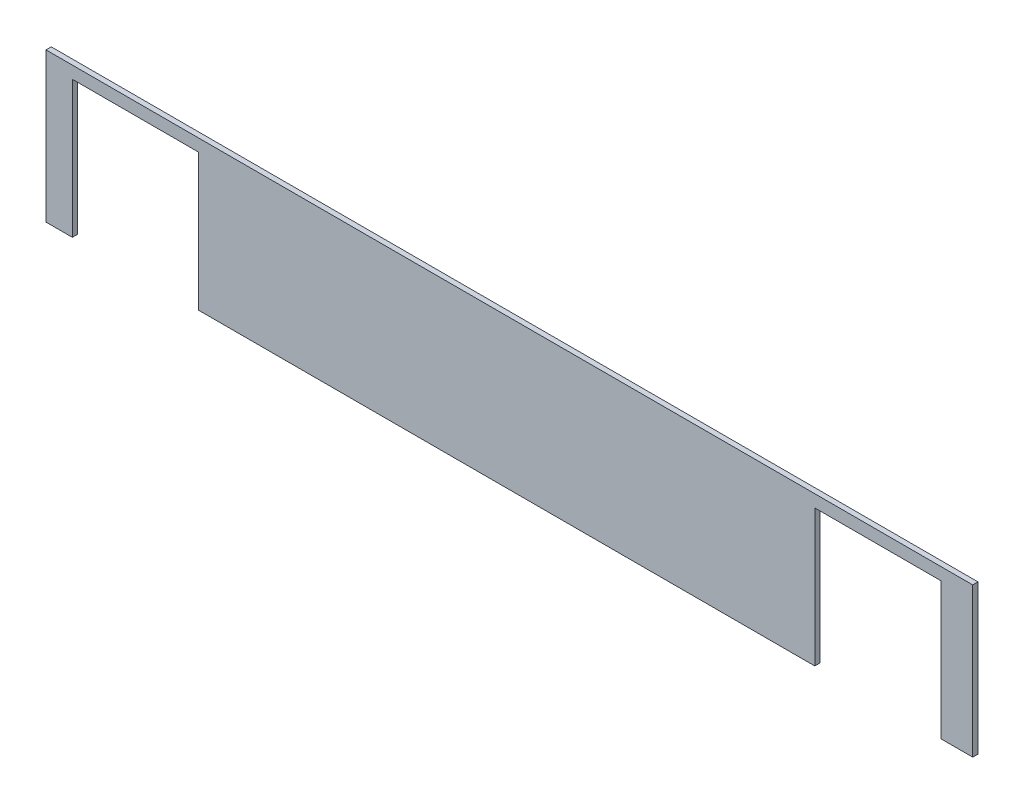
SolidWorks part; units mm, degrees
ref_plane "Front Plane" through (0, 0, 0) normal (0, 0, 1) x (1, 0, 0)
ref_plane "Top Plane" through (0, 0, 0) normal (0, 1, 0) x (1, 0, 0)
ref_plane "Right Plane" through (0, 0, 0) normal (1, 0, 0) x (0, 0, -1)
sketch "Sketch2" plane through (0, 0, 0) normal (0, 0, 1) x (1, 0, 0)
  line L1 (0, 0) -> (13411.2, 0)
  line L2 (0, 0) -> (0, 2159)
  line L3 (0, 2159) -> (13411.2, 2159)
  line L4 (13411.2, 0) -> (13411.2, 2159)
  dimension "D1" = 13411.2
  dimension "D2" = 2159
extrude "Boss-Extrude1" add sketch "Sketch2" along normal blind 76.2
sketch "Sketch3" plane through (0, 0, 0) normal (0, 0, -1) x (-1, 0, 0)
  line L0 (0, 0) -> (-13411.2, 0) construction
  line L1 (-12954, 0) -> (-11125.2, 0)
  line L2 (-12954, 0) -> (-12954, 1981.2)
  line L3 (-12954, 1981.2) -> (-11125.2, 1981.2)
  line L4 (-11125.2, 0) -> (-11125.2, 1981.2)
  line L5 (-13335, 0) -> (-13335, 1028.7) construction
  line L6 (-381, 0) -> (-2209.8, 0)
  line L7 (-381, 0) -> (-381, 1981.2)
  line L8 (-381, 1981.2) -> (-2209.8, 1981.2)
  line L9 (-2209.8, 0) -> (-2209.8, 1981.2)
  line L10 (0, 0) -> (0, 2159) construction
  dimension "D1" = 381
  dimension "D2" = 1828.8
  dimension "D3" = 1828.8
  dimension "D4" = 381
  dimension "D5" = 1981.2
  dimension "D6" = 1981.2
extrude "Cut-Extrude1" cut sketch "Sketch3" against normal through all
